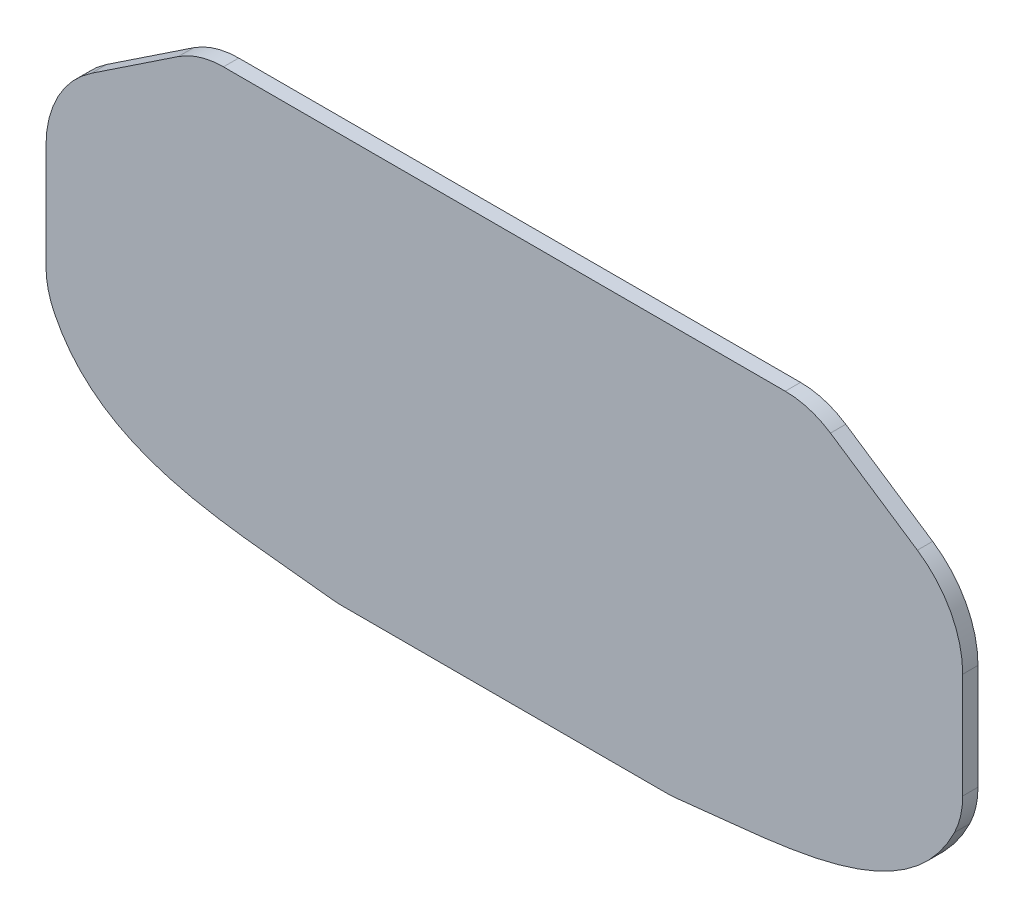
SolidWorks part; units mm, degrees
ref_plane "Front Plane" through (0, 0, 0) normal (0, 0, 1) x (1, 0, 0)
ref_plane "Top Plane" through (0, 0, 0) normal (0, 1, 0) x (1, 0, 0)
ref_plane "Right Plane" through (0, 0, 0) normal (1, 0, 0) x (0, 0, -1)
sketch "Sketch1" plane through (0, 0, 0) normal (0, 0, 1) x (1, 0, 0)
  line L0 (0, 76.2) -> (38.1, 101.6)
  line L1 (38.1, 101.6) -> (190.5, 101.6)
  line L2 (190.5, 101.6) -> (228.6, 76.2)
  line L3 (228.6, 76.2) -> (228.6, 0)
  line L4 (228.6, 0) -> (0, 0)
  line L5 (0, 0) -> (0, 76.2)
  dimension "D1" = 152.4
  dimension "D2" = 38.1
  dimension "D3" = 38.1
  dimension "D4" = 25.4
  dimension "D5" = 25.4
  dimension "D6" = 101.6
extrude "Boss-Extrude1" add sketch "Sketch1" along normal blind 3.81 contours L1 L2 L3 L4 L5 L0
fillet "Fillet1" radius 20.32 2 edges at (38.1, 101.6, 1.905) (190.5, 101.6, 1.905)
fillet "Fillet3" radius 25.4 2 edges at (228.6, 76.2, 1.905) (0, 76.2, 1.905)
sketch "Sketch2" plane through (0, 0, 3.81) normal (0, 0, 1) x (1, 0, 0)
  line L0 (0, -55) -> (0, 55) construction
  line L2 (72.3248, 0) -> (0, 0)
  line L3 (0, 0) -> (0, 32.4837)
  line L4 (114.3, 123.048) -> (114.3, -17.9761) construction
  line L5 (156.2752, 0) -> (228.6, 0)
  line L6 (228.6, 0) -> (228.6, 32.4837)
  spline S0 degree 3 poles (0, 32.4837) (10.0595, 1.8404) (47.8361, 3.417) (72.3248, 0) knots 0 0 0 0 1 1 1 1
  spline S1 degree 3 poles (228.6, 32.4837) (218.5405, 1.8404) (180.7639, 3.417) (156.2752, 0) knots 0 0 0 0 1 1 1 1
  dimension "D1" = 114.3
extrude "Cut-Extrude8" cut sketch "Sketch2" against normal through all contours S0 L2 L3 | L5 L6 S1
fillet "Fillet4" radius 20.32 2 edges at (0, 32.4837, 1.905) (228.6, 32.4837, 1.905)
fillet "Fillet5" radius 20.32 2 edges at (156.2752, 0, 1.905) (72.3248, 0, 1.905)
